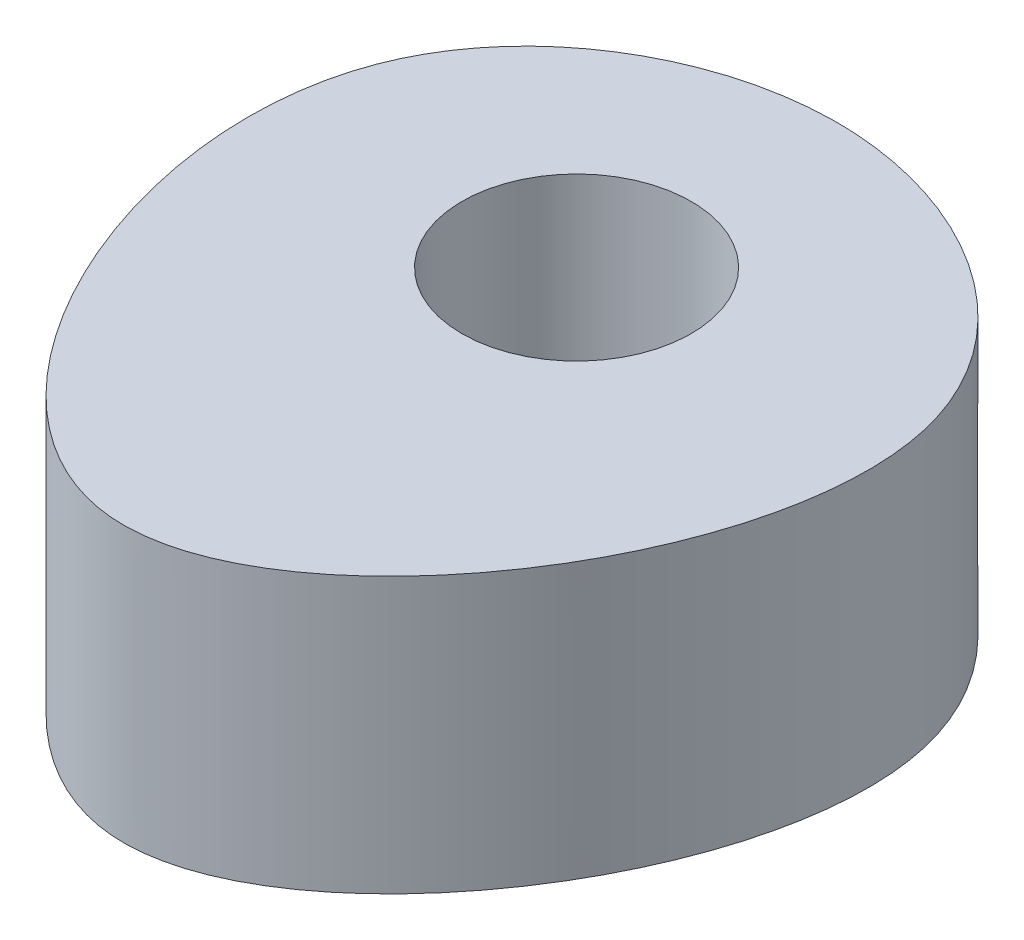
SolidWorks part; units mm, degrees
ref_plane "Front Plane" through (0, 0, 0) normal (0, 0, 1) x (1, 0, 0)
ref_plane "Top Plane" through (0, 0, 0) normal (0, 1, 0) x (1, 0, 0)
ref_plane "Right Plane" through (0, 0, 0) normal (1, 0, 0) x (0, 0, -1)
sketch "Sketch1" plane through (0, 0, 0) normal (0, 1, 0) x (1, 0, 0)
  circle A0 centre (0, 0) radius 12.5
  spline S0 degree 3 poles (54.0444, 4.0707) (1.56, 36.2406) (-47.951, 7.0061) (-3.5855, -83.1883) (54.0444, 4.0707) (1.56, 36.2406) (-47.951, 7.0061) knots -0.826368 -0.513369 -0.200076 0 0.173632 0.486631 0.799924 1 1.173632 1.486631 1.799924 only from (0, 27.9028) to (0, 27.9028)
  dimension "D1" = 25
  dimension "D2" = 34
  dimension "D3" = 30
  dimension "D4" = 49
extrude "Boss-Extrude1" add sketch "Sketch1" along normal blind 30
